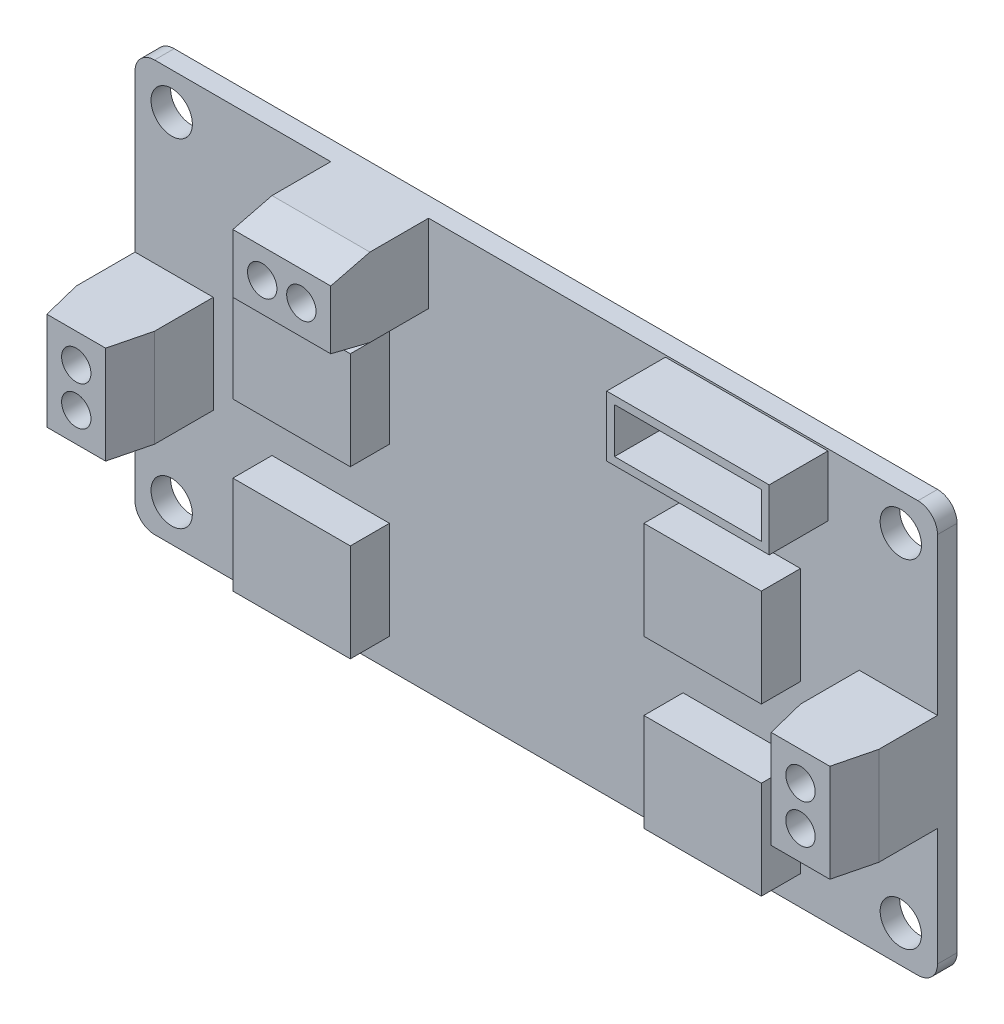
SolidWorks part; units mm, degrees
ref_plane "前视基准面" through (0, 0, 0) normal (0, 0, 1) x (1, 0, 0)
ref_plane "上视基准面" through (0, 0, 0) normal (0, 1, 0) x (1, 0, 0)
ref_plane "右视基准面" through (0, 0, 0) normal (1, 0, 0) x (0, 0, -1)
sketch "草图1" plane through (0, 0, 0) normal (0, 0, 1) x (1, 0, 0)
  line L1 (-39, 21) -> (39, 21)
  line L2 (-41, 19) -> (-41, -19)
  line L3 (-39, -21) -> (39, -21)
  line L4 (41, 19) -> (41, -19)
  line L5 (-41, 21) -> (41, -21) construction
  line L6 (-41, -21) -> (41, 21) construction
  arc A0 (41, 19) -> (39, 21) centre (39, 19) ccw
  arc A1 (39, -21) -> (41, -19) centre (39, -19) ccw
  arc A2 (-39, -21) -> (-41, -19) centre (-39, -19) cw
  arc A3 (-41, 19) -> (-39, 21) centre (-39, 19) cw
  point P0 (0, 0)
  dimension "D3" = 2
  dimension "D1" = 82
  dimension "D2" = 42
extrude "凸台-拉伸1" add sketch "草图1" along normal blind 2
sketch "草图2" plane through (0, 0, 2) normal (0, 0, 1) x (1, 0, 0)
  line L0 (39, 21) -> (-39, 21) construction
  line L1 (-41, 19) -> (-41, -19) construction
  circle A0 centre (-37.25, 17.25) radius 2.1123
  dimension "D1" = 3.75
  dimension "D2" = 3.75
extrude "切除-拉伸1" cut sketch "草图2" against normal blind 2
mirror "镜向1" about plane through (0, 0, 0) normal (0, 1, 0) of "切除-拉伸1"
mirror "镜向2" about plane through (0, 0, 0) normal (1, 0, 0) of "镜向1", "切除-拉伸1"
sketch "草图3" plane through (0, 0, 2) normal (0, 0, 1) x (1, 0, 0)
  line L0 (-41, 19) -> (-41, -19) construction
  line L1 (-41, 3) -> (-33, 3)
  line L2 (-41, 3) -> (-41, -7)
  line L3 (-41, -7) -> (-33, -7)
  line L4 (-33, 3) -> (-33, -7)
  dimension "D1" = 3
  dimension "D2" = 8
  dimension "D3" = 10
extrude "凸台-拉伸2" add sketch "草图3" along normal blind 10
sketch "草图4" plane through (0, -7, 0) normal (0, -1, 0) x (1, 0, 0)
  line L0 (-40, 12) -> (-41, 8)
  line L1 (-41, 12) -> (-33, 12) construction
  line L2 (-41, 12) -> (-41, 2) construction
  line L3 (-37, 12) -> (-37, 8.2088) construction
  line L4 (-41, 8) -> (-41, 12)
  line L5 (-41, 12) -> (-40, 12)
  line L6 (-33, 12) -> (-34, 12)
  line L7 (-33, 8) -> (-33, 12)
  line L8 (-34, 12) -> (-33, 8)
  dimension "D1" = 1
  dimension "D2" = 4
extrude "切除-拉伸2" cut sketch "草图4" against normal blind 10
sketch "草图5" plane through (0, 0, 12) normal (0, 0, 1) x (1, 0, 0)
  line L0 (-33, 3) -> (-41, 3) construction
  line L2 (-40, -7) -> (-34, -7) construction
  line L3 (-34, 3) -> (-34, -7) construction
  circle A0 centre (-37, 0) radius 1.5
  circle A1 centre (-37, -4) radius 1.5
  point P6 (-37, -7)
  dimension "D1" = 3
  dimension "D2" = 3
  dimension "D3" = 3
  dimension "D4" = 3
  dimension "D5" = 3
extrude "切除-拉伸3" cut sketch "草图5" against normal blind 8
mirror "镜向3" about plane through (0, 0, 0) normal (1, 0, 0) of "切除-拉伸2", "凸台-拉伸2", "切除-拉伸3"
sketch "草图6" plane through (0, 0, 2) normal (0, 0, 1) x (1, 0, 0)
  line L0 (39, 21) -> (-39, 21) construction
  line L1 (-21, 21) -> (-11, 21)
  line L2 (-21, 21) -> (-21, 13)
  line L3 (-21, 13) -> (-11, 13)
  line L4 (-11, 21) -> (-11, 13)
  line L5 (-41, 19) -> (-41, 3) construction
  dimension "D1" = 20
  dimension "D2" = 10
  dimension "D3" = 8
extrude "凸台-拉伸3" add sketch "草图6" along normal blind 10
sketch "草图7" plane through (-21, 0, 0) normal (-1, 0, 0) x (0, 0, 1)
  line L0 (8, 21) -> (12, 20)
  line L1 (12, 21) -> (2, 21) construction
  line L2 (12, 21) -> (12, 13) construction
  line L3 (12, 20) -> (12, 21)
  line L4 (12, 21) -> (8, 21)
  line L5 (12, 17) -> (5.8887, 17) construction
  line L6 (12, 13) -> (8, 13)
  line L7 (12, 14) -> (12, 13)
  line L8 (8, 13) -> (12, 14)
  dimension "D1" = 4
  dimension "D2" = 1
extrude "切除-拉伸4" cut sketch "草图7" against normal blind 10
sketch "草图8" plane through (0, 0, 12) normal (0, 0, 1) x (1, 0, 0)
  line L0 (-11, 13) -> (-11, 21) construction
  line L1 (-21, 20) -> (-21, 14) construction
  line L2 (-11, 14) -> (-21, 14) construction
  circle A0 centre (-14, 17) radius 1.5
  circle A1 centre (-18, 17) radius 1.5
  dimension "D1" = 3
  dimension "D2" = 3
  dimension "D3" = 3
  dimension "D4" = 3
  dimension "D5" = 3
extrude "切除-拉伸5" cut sketch "草图8" against normal blind 8
sketch "草图9" plane through (0, 0, 2) normal (0, 0, 1) x (1, 0, 0)
  line L0 (39, 21) -> (-11, 21) construction
  line L1 (14, 20) -> (29, 20)
  line L2 (14, 20) -> (14, 15.4038)
  line L3 (14, 15.4038) -> (29, 15.4038)
  line L4 (29, 20) -> (29, 15.4038)
  line L5 (41, 3) -> (41, 19) construction
  dimension "D1" = 1
  dimension "D2" = 12
  dimension "D3" = 15
extrude "拉伸-薄壁1" add sketch "草图9" along normal blind 6 thin thin type one direction wall 0.8
sketch "草图10" plane through (0, 0, 2) normal (0, 0, 1) x (1, 0, 0)
  line L0 (-21, 21) -> (-39, 21) construction
  line L1 (-27, 9) -> (-15, 9)
  line L2 (-27, 9) -> (-27, -1)
  line L3 (-27, -1) -> (-15, -1)
  line L4 (-15, 9) -> (-15, -1)
  line L5 (-41, 19) -> (-41, 3) construction
  dimension "D1" = 12
  dimension "D2" = 10
  dimension "D3" = 12
  dimension "D4" = 14
extrude "凸台-拉伸4" add sketch "草图10" along normal blind 4
sketch "草图12" plane through (0, 0, 2) normal (0, 0, 1) x (1, 0, 0)
  line L0 (-39, -21) -> (39, -21) construction
  line L1 (-27, -8) -> (-15, -8)
  line L2 (-27, -8) -> (-27, -18)
  line L3 (-27, -18) -> (-15, -18)
  line L4 (-15, -8) -> (-15, -18)
  dimension "D1" = 12
  dimension "D2" = 10
  dimension "D3" = 3
extrude "凸台-拉伸5" add sketch "草图12" along normal blind 4
mirror "镜向4" about plane through (0, 0, 0) normal (1, 0, 0) of "凸台-拉伸4", "凸台-拉伸5"
